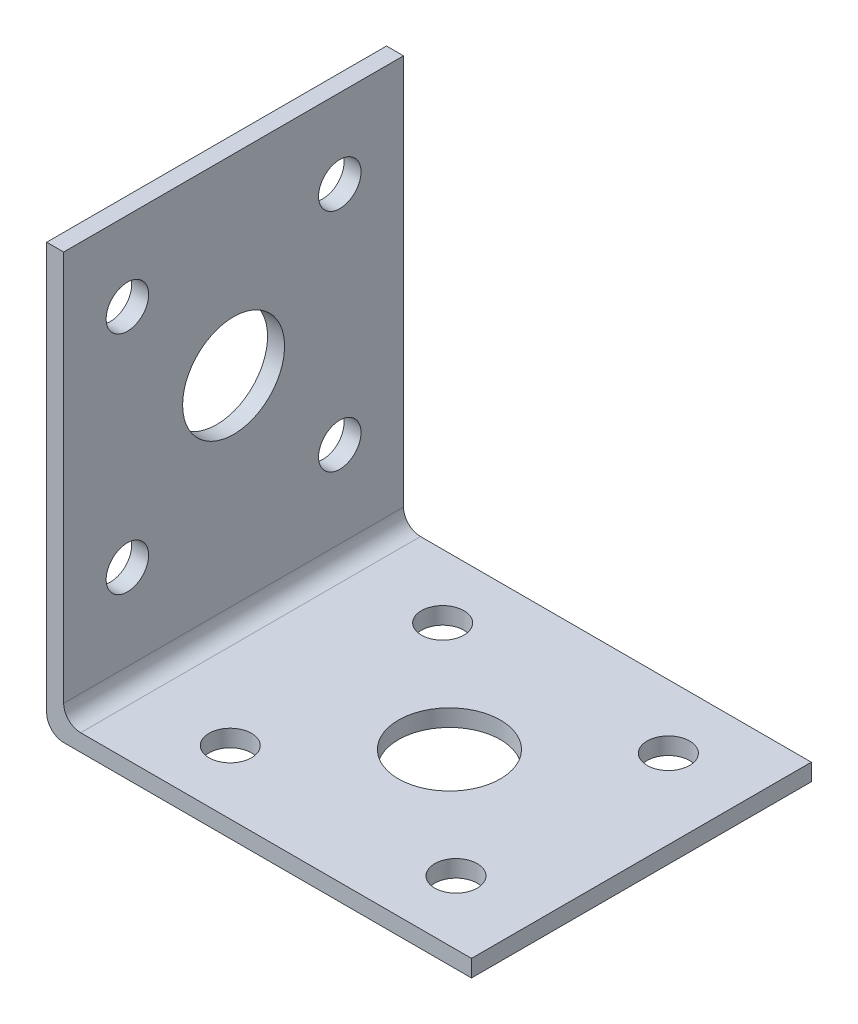
SolidWorks part; units mm, degrees
ref_plane "Front Plane" through (0, 0, 0) normal (0, 0, 1) x (1, 0, 0)
ref_plane "Top Plane" through (0, 0, 0) normal (0, 1, 0) x (1, 0, 0)
ref_plane "Right Plane" through (0, 0, 0) normal (1, 0, 0) x (0, 0, -1)
sketch "Sketch1" plane through (0, 0, 0) normal (0, 0, 1) x (1, 0, 0)
  line L0 (0, 2) -> (0, 50)
  line L1 (0, 50) -> (2, 50)
  line L2 (2, 50) -> (2, 4)
  line L3 (4, 2) -> (50, 2)
  line L4 (50, 2) -> (50, 0)
  line L5 (50, 0) -> (2, 0)
  arc A0 (2, 4) -> (4, 2) centre (4, 4) ccw
  arc A1 (0, 2) -> (2, 0) centre (2, 2) ccw
  point P11 (0, 0)
  dimension "D5" = 2
  dimension "D1" = 50
  dimension "D2" = 50
  dimension "D3" = 2
  dimension "D4" = 2
extrude "Boss-Extrude1" add sketch "Sketch1" along normal mid plane 40
sketch "Sketch2" plane through (0, 0, 0) normal (0, 1, 0) x (1, 0, 0)
  line L0 (0, 20) -> (0, -20) construction
ref_plane "Plane1" through (0, 0, 0) normal (-0.7071, 0.7071, 0) x (0, 0, 1)
sketch "Sketch3" plane through (0, 2, 0) normal (0, 1, 0) x (1, 0, 0)
  line L0 (50, -20) -> (50, 20) construction
  line L1 (14.1076, 12.5) -> (14.1076, -12.5) construction
  line L2 (50, 0) -> (0, 0) construction
  line L3 (40.6751, 12.5) -> (40.6751, -12.5) construction
  circle A0 centre (27.4054, 0) radius 6
  circle A1 centre (40.6751, 12.5) radius 2.5
  circle A2 centre (40.6751, -12.5) radius 2.5
  circle A3 centre (14.1076, -12.5) radius 2.5
  circle A4 centre (14.1076, 12.5) radius 2.5
  point P15 (14.1076, 0)
  point P16 (40.6751, 0)
  dimension "D1" = 5
  dimension "D2" = 5
  dimension "D3" = 5
  dimension "D4" = 5
  dimension "D7" = 12
  dimension "D5" = 25
  dimension "D6" = 25
extrude "Cut-Extrude1" cut sketch "Sketch3" against normal blind 40
mirror "Mirror1" about plane through (0, 0, 0) normal (-0.7071, 0.7071, 0) of "Cut-Extrude1"
